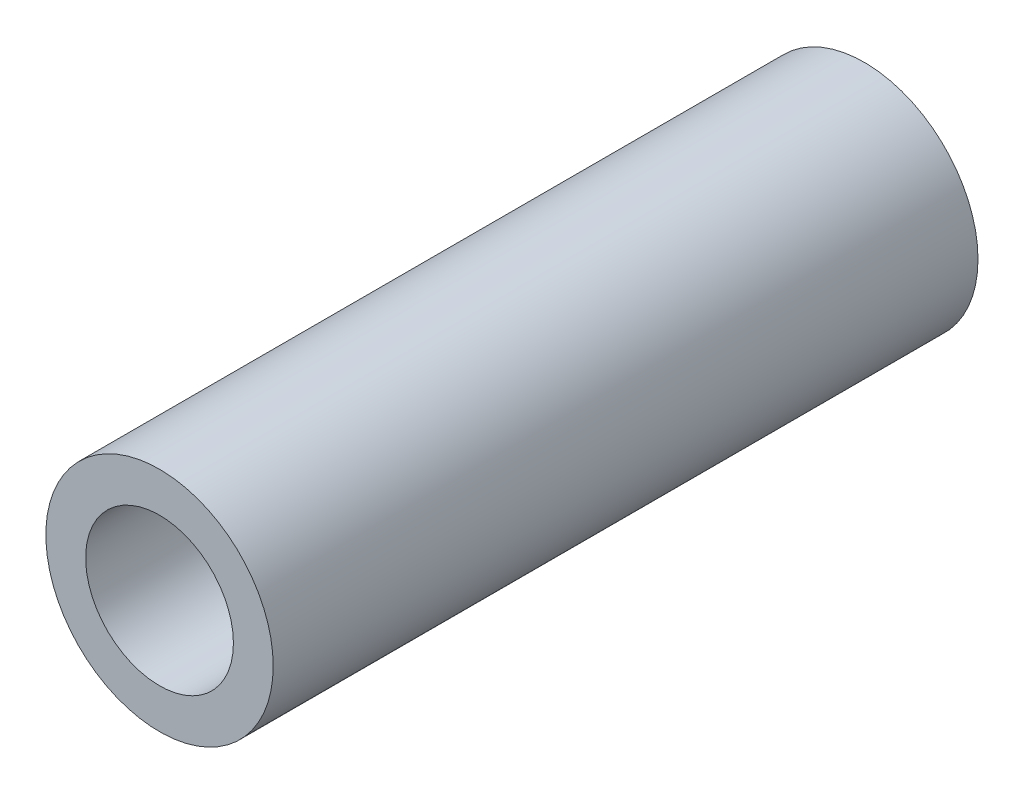
SolidWorks part; units mm, degrees
material "ABS"
ref_plane "Plan de face" through (0, 0, 0) normal (0, 0, 1) x (1, 0, 0)
ref_plane "Plan de dessus" through (0, 0, 0) normal (0, 1, 0) x (1, 0, 0)
ref_plane "Plan de droite" through (0, 0, 0) normal (1, 0, 0) x (0, 0, -1)
sketch "Esquisse1" plane through (0, 0, 0) normal (0, 0, 1) x (1, 0, 0)
  circle A0 centre (0, 0) radius 6.5
  circle A1 centre (0, 0) radius 10
  dimension "D1" = 13
  dimension "D2" = 20
extrude "Boss.-Extru.1" add sketch "Esquisse1" along normal blind 62
